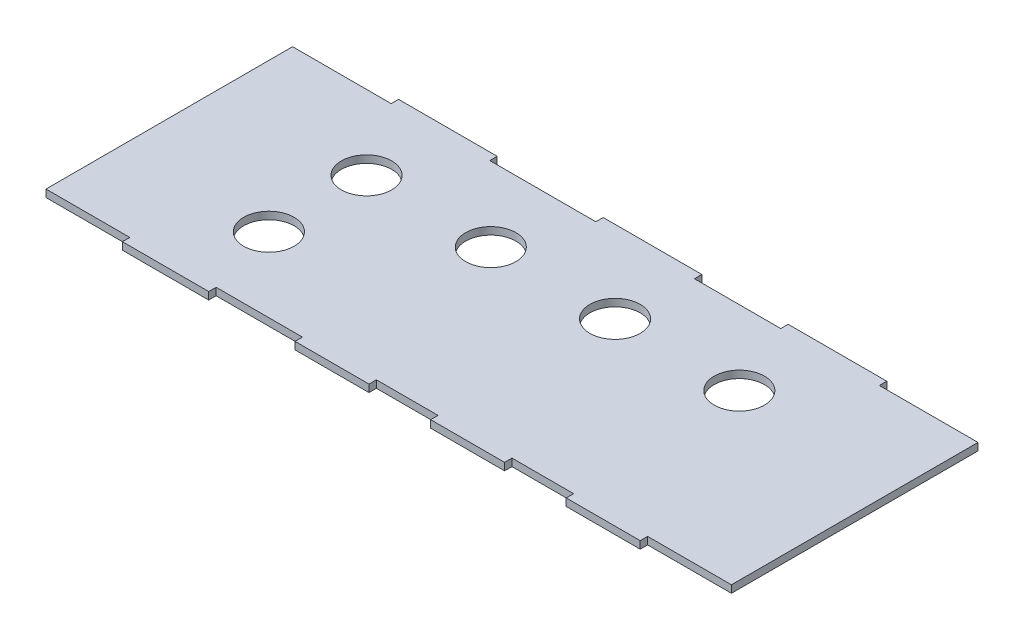
SolidWorks part; units mm, degrees
ref_plane "Front Plane" through (0, 0, 0) normal (0, 0, 1) x (1, 0, 0)
ref_plane "Top Plane" through (0, 0, 0) normal (0, 1, 0) x (1, 0, 0)
ref_plane "Right Plane" through (0, 0, 0) normal (1, 0, 0) x (0, 0, -1)
sketch "Sketch1" plane through (0, 0, 0) normal (0, 1, 0) x (1, 0, 0)
  line L1 (-139, 50) -> (139, 50)
  line L2 (-139, 50) -> (-139, -50)
  line L3 (-139, -50) -> (139, -50)
  line L4 (139, 50) -> (139, -50)
  dimension "D1" = 278
  dimension "D2" = 100
  dimension "D3" = 50
  dimension "D4" = 139
extrude "Boss-Extrude1" add sketch "Sketch1" along normal blind 3
sketch "Sketch2" plane through (0, 0, -50) normal (0, 0, -1) x (-1, 0, 0)
  line L0 (-139, 0) -> (139, 0) construction
  line L1 (-99, 0) -> (-59, 0)
  line L2 (-99, 0) -> (-99, 3)
  line L3 (-99, 3) -> (-59, 3)
  line L4 (-59, 0) -> (-59, 3)
  line L5 (-99, 0) -> (-59, 0) construction
  line L6 (-139, 3) -> (139, 3) construction
  line L7 (-59, 0) -> (-59, 3) construction
  line L8 (-24, 0) -> (-24, 3) construction
  line L9 (-24, 0) -> (16, 0)
  line L10 (-24, 0) -> (-24, 3)
  line L11 (-24, 3) -> (16, 3)
  line L12 (16, 0) -> (16, 3)
  line L13 (16, 0) -> (16, 3) construction
  line L14 (59, 0) -> (59, 3) construction
  line L15 (59, 0) -> (99, 0)
  line L16 (59, 0) -> (59, 3)
  line L17 (59, 3) -> (99, 3)
  line L18 (99, 0) -> (99, 3)
  line L19 (99, 0) -> (99, 3) construction
  line L20 (-99, 0) -> (-99, 3) construction
extrude "Boss-Extrude2" add sketch "Sketch2" along normal blind 3
sketch "Sketch3" plane through (0, 3, 0) normal (0, 1, 0) x (1, 0, 0)
  line L2 (-139, 50) -> (-139, -50) construction
  line L3 (-138, 50) -> (-99, 50) construction
  line L7 (-139, -50) -> (139, -50) construction
  circle A0 centre (72.4, 19.8) radius 10.2
  circle A1 centre (-78.8, -19.8) radius 10.2
  circle A2 centre (22, 19.8) radius 10.2
  circle A3 centre (-28.4, 19.8) radius 10.2
  circle A4 centre (-78.8, 19.8) radius 10.2
  dimension "D1" = 20.4
  dimension "D2" = 20.4
  dimension "D3" = 20.4
  dimension "D4" = 20.4
  dimension "D5" = 20.4
  dimension "D9" = 50
  dimension "D10" = 20
  dimension "D11" = 50
  dimension "D12" = 20
  dimension "D6" = 30
  dimension "D7" = 30
  dimension "D8" = 30
extrude "Cut-Extrude1" cut sketch "Sketch3" against normal blind 3
sketch "Sketch4" plane through (0, 0, 50) normal (0, 0, 1) x (1, 0, 0)
  line L0 (-139, 0) -> (139, 0) construction
  line L1 (-105, 0) -> (-70, 0)
  line L2 (-105, 0) -> (-105, 3)
  line L3 (-105, 3) -> (-70, 3)
  line L4 (-70, 0) -> (-70, 3)
  line L5 (-105, 3) -> (-105, 0) construction
  line L6 (-139, 3) -> (139, 3) construction
  line L7 (-70, 0) -> (-70, 3) construction
  line L8 (-35, 3) -> (-35, 0) construction
  line L9 (-35, 3) -> (-5, 3)
  line L10 (-35, 3) -> (-35, 0)
  line L11 (-35, 0) -> (-5, 0)
  line L12 (-5, 3) -> (-5, 0)
  line L13 (-5, 0) -> (-5, 3) construction
  line L14 (20, 3) -> (20, 0) construction
  line L15 (20, 3) -> (50, 3)
  line L16 (20, 3) -> (20, 0)
  line L17 (20, 0) -> (50, 0)
  line L18 (50, 3) -> (50, 0)
  line L19 (50, 0) -> (50, 3) construction
  line L20 (75, 3) -> (75, 0) construction
  line L21 (75, 3) -> (105, 3)
  line L22 (75, 3) -> (75, 0)
  line L23 (75, 0) -> (105, 0)
  line L24 (105, 3) -> (105, 0)
  line L25 (105, 0) -> (105, 3) construction
extrude "Boss-Extrude3" add sketch "Sketch4" along normal blind 3
